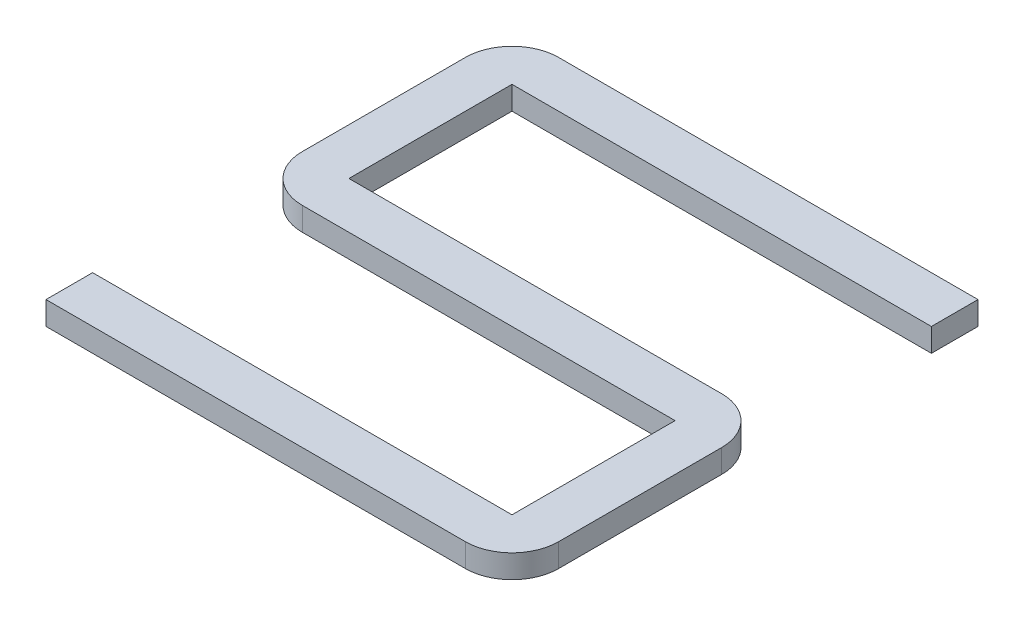
SolidWorks part; units mm, degrees
ref_plane "Front Plane" through (0, 0, 0) normal (0, 0, 1) x (1, 0, 0)
ref_plane "Top Plane" through (0, 0, 0) normal (0, 1, 0) x (1, 0, 0)
ref_plane "Right Plane" through (0, 0, 0) normal (1, 0, 0) x (0, 0, -1)
sketch "Sketch2" plane through (0, 0, 0) normal (0, 1, 0) x (1, 0, 0)
  line L0 (20, 20) -> (20, 16)
  line L1 (-16, 20) -> (20, 20)
  line L2 (-20, 16) -> (-20, 2)
  line L3 (-20, -20) -> (16, -20)
  line L5 (-20, -16) -> (-20, -20)
  line L6 (20, -2) -> (20, -16)
  line L7 (20, 16) -> (-16, 16)
  line L8 (20, 20) -> (17.9715, 20) construction
  line L9 (16, -16) -> (-20, -16)
  line L11 (-16, 16) -> (-16, 2)
  line L12 (16, -2) -> (16, -16)
  line L15 (16, -2) -> (-16, -2)
  line L25 (-16, 2) -> (16, 2)
  arc A0 (-16, 20) -> (-20, 16) centre (-16, 16) ccw
  arc A1 (-20, 2) -> (-16, -2) centre (-16, 2) ccw
  arc A2 (16, 2) -> (20, -2) centre (16, -2) cw
  arc A3 (16, -20) -> (20, -16) centre (16, -16) ccw
  point P0 (0, 0)
  point P18 (0, 0)
extrude "Boss-Extrude1" add sketch "Sketch2" along normal blind 2
